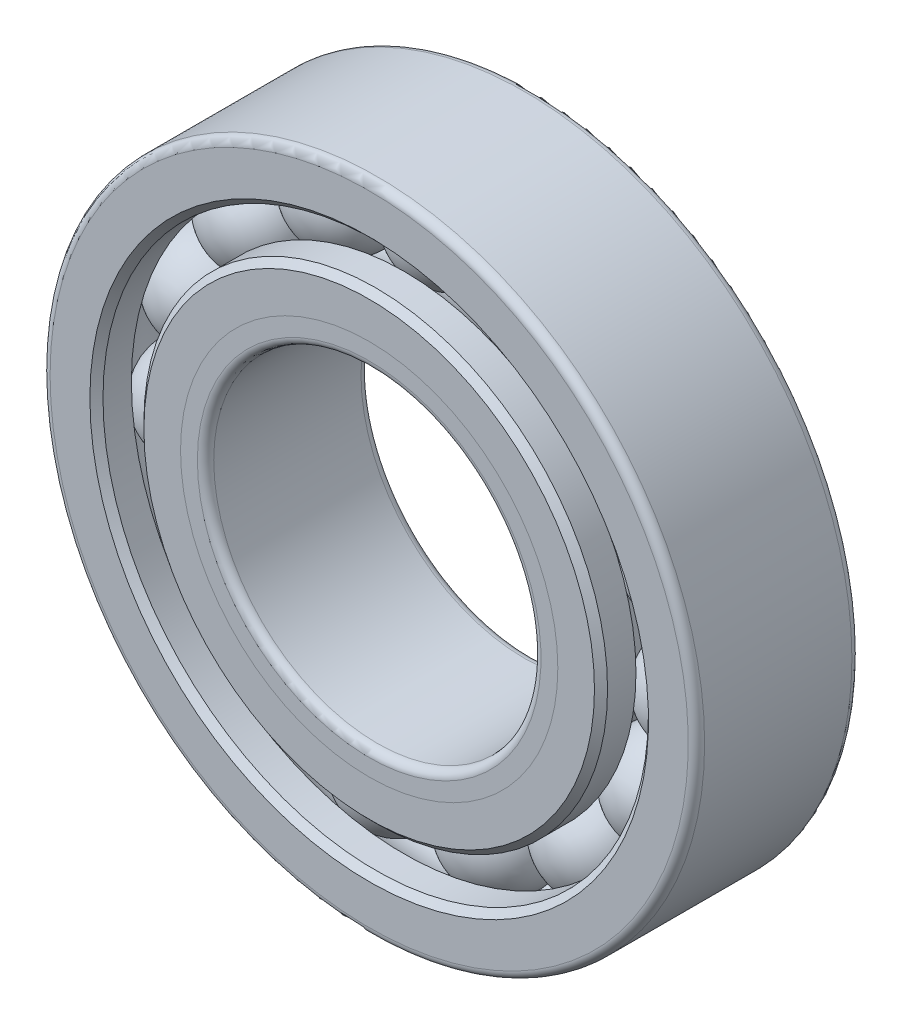
SolidWorks part; units mm, degrees
ref_plane "Front Plane" through (0, 0, 0) normal (0, 0, 1) x (1, 0, 0)
ref_plane "Top Plane" through (0, 0, 0) normal (0, 1, 0) x (1, 0, 0)
ref_plane "Right Plane" through (0, 0, 0) normal (1, 0, 0) x (0, 0, -1)
sketch "Sketch1" plane through (0, 0, 0) normal (1, 0, 0) x (0, 0, -1)
  line L0 (-6.35, 0) -> (6.35, 0) construction
  line L9 (0, 25.4) -> (0, 0) construction
  line L10 (-6.35, 12.7) -> (6.35, 12.7)
  line L11 (6.35, 12.7) -> (6.35, 17.9934)
  line L12 (6.35, 17.9934) -> (-6.35, 17.9934)
  line L13 (-6.35, 17.9934) -> (-6.35, 12.7)
  line L14 (-6.35, 21.1684) -> (6.35, 21.1684)
  line L15 (6.35, 21.1684) -> (6.35, 25.4)
  line L16 (6.35, 25.4) -> (-6.35, 25.4)
  line L17 (-6.35, 25.4) -> (-6.35, 21.1684)
  line L18 (-3.9687, 19.5809) -> (3.9687, 19.5809) construction
  line L20 (6.35, 14.6414) -> (-6.35, 14.6414) construction
  line L21 (0, 15.6121) -> (0, 14.6414)
  line L22 (0, 14.6414) -> (0, 13.6707)
  line L23 (0, 13.6707) -> (0, 12.7)
  circle A0 centre (0, 19.5809) radius 3.9688
  point P17 (0, 23.5496)
  dimension "ID" = 25.4
  dimension "OD" = 50.8
  dimension "Ball Diameter" = 7.9375
  dimension "Ball Pattern Diameter" = 39.1617
  dimension "D6" = 3.175
  dimension "Width" = 12.7
sketch "Sketch2" plane through (0, 0, 0) normal (0, 0, 1) x (1, 0, 0)
  circle A0 centre (0, 0) radius 19.5809 construction
  circle A1 centre (0, 19.5809) radius 3.9688
  circle A2 centre (7.9643, 17.888) radius 3.9688
  circle A3 centre (14.5514, 13.1022) radius 3.9688
  circle A4 centre (18.6225, 6.0508) radius 3.9688
  circle A5 centre (19.4736, -2.0468) radius 3.9688
  circle A6 centre (16.9575, -9.7904) radius 3.9688
  circle A7 centre (11.5093, -15.8412) radius 3.9688
  circle A8 centre (4.0711, -19.153) radius 3.9688
  circle A9 centre (-4.0711, -19.153) radius 3.9688
  circle A10 centre (-11.5093, -15.8412) radius 3.9688
  circle A11 centre (-16.9575, -9.7904) radius 3.9688
  circle A12 centre (-19.4736, -2.0468) radius 3.9688
  circle A13 centre (-18.6225, 6.0508) radius 3.9688
  circle A15 centre (0, 0) radius 12.7 construction
  circle A16 centre (0, 0) radius 25.4 construction
  circle A17 centre (-14.5514, 13.1022) radius 3.9687
  circle A18 centre (-7.9643, 17.888) radius 3.9688
  point P36 (0, 0)
  dimension "ID" = 25.4
  dimension "OD" = 50.8
  dimension "No. of Balls" = 15
sketch "Sketch3" plane through (0, 0, 0) normal (1, 0, 0) x (0, 0, -1)
  line L1 (6.35, 12.7) -> (6.35, 17.9934) construction
  line L2 (-6.35, 17.9934) -> (-6.35, 12.7) construction
  line L3 (6.35, 17.9934) -> (-6.35, 17.9934) construction
  line L5 (6.35, 12.7) -> (6.35, 17.9934)
  line L6 (-6.35, 17.9934) -> (-6.35, 12.7)
  line L7 (6.35, 17.9934) -> (-6.35, 17.9934)
  line L8 (-6.35, 25.4) -> (-6.35, 21.1684) construction
  line L9 (6.35, 25.4) -> (-6.35, 25.4) construction
  line L10 (6.35, 21.1684) -> (6.35, 25.4) construction
  line L11 (-6.35, 21.1684) -> (6.35, 21.1684) construction
  line L12 (-6.35, 25.4) -> (-6.35, 21.1684)
  line L13 (6.35, 25.4) -> (-6.35, 25.4)
  line L14 (6.35, 21.1684) -> (6.35, 25.4)
  line L15 (-6.35, 21.1684) -> (6.35, 21.1684)
  line L16 (-6.35, 12.7) -> (6.35, 12.7) construction
  line L17 (-6.35, 12.7) -> (6.35, 12.7)
revolve "Revolve2" add sketch "Sketch3" angle 360 about L0
sketch "Sketch4" plane through (0, 0, 0) normal (1, 0, 0) x (0, 0, -1)
  circle A0 centre (0, 19.5809) radius 3.9688 construction
  circle A1 centre (0, 19.5809) radius 3.9688
revolve "Cut-Revolve1" cut sketch "Sketch4" angle 360 about L0
sketch "Sketch5" plane through (0, 0, 0) normal (1, 0, 0) x (0, 0, -1)
  line L0 (-3.9687, 19.5809) -> (3.9687, 19.5809) construction
  line L1 (-3.9687, 19.5809) -> (3.9687, 19.5809)
  circle A0 centre (0, 19.5809) radius 3.9688 construction
  arc A1 (3.9687, 19.5809) -> (-3.9687, 19.5809) centre (0, 19.5809) ccw
revolve "Revolve3" add sketch "Sketch5" angle 360 about L18
pattern_circular "CirPattern1" count 15 over 360 about axis through (0, 0, 0) along (0, 0, 1) of bodies 109
fillet "Fillet1" radius 0.635 2 edges at (25.4, 0, 6.35) (25.4, 0, -6.35)
fillet "Fillet2" radius 0.635 2 edges at (12.7, 0, -6.35) (12.7, 0, 6.35)
chamfer "Chamfer1" distance 0.508 angle 45 2 edges at (21.1684, 0, -6.35) (21.1684, 0, 6.35)
chamfer "Chamfer2" distance 0.508 angle 45 2 edges at (17.9934, 0, 6.35) (17.9934, 0, -6.35)
sketch "Split Line" plane through (0, 0, 0) normal (0, 0, 1) x (1, 0, 0)
  circle A0 centre (0, 0) radius 14.6414
split "Split1" trim tools "Split Line" bodies to split 108 resulting bodies 128 129
equation "\"D1@CirPattern1\"=\"No. of Balls@Sketch2\""
equation "\"D6@Sketch1\"=\"Ball Diameter@Sketch1\"*0.4"
equation "\"D1@Fillet1\"=\"Width@Sketch1\"/20"
equation "\"D1@Fillet2\"=\"Width@Sketch1\"/20"
equation "\"D1@Chamfer1\"=\"Width@Sketch1\"/25"
equation "\"D1@Chamfer2\"=\"Width@Sketch1\"/25"
equation "\"ID@Sketch2\"=\"ID@Sketch1\""
equation "\"OD@Sketch2\" = \"OD@Sketch1\""
